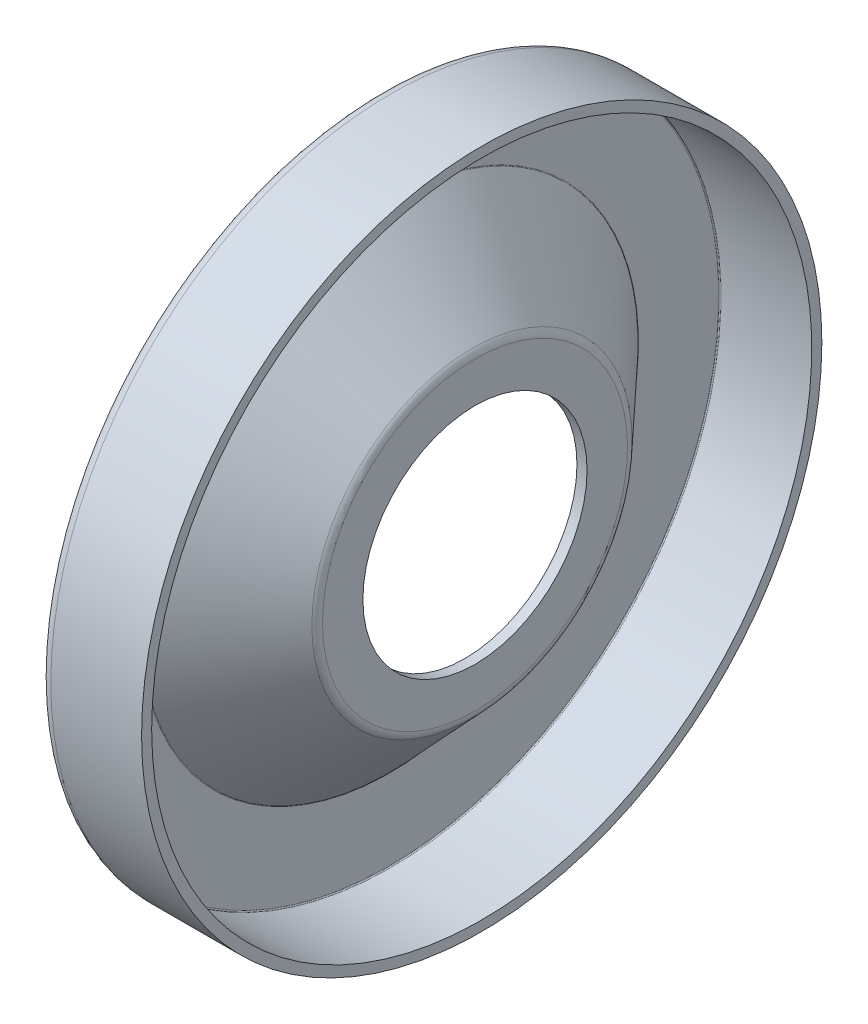
SolidWorks part; units mm, degrees
ref_plane "Alzado" through (0, 0, 0) normal (0, 0, 1) x (1, 0, 0)
ref_plane "Planta" through (0, 0, 0) normal (0, 1, 0) x (1, 0, 0)
ref_plane "Vista lateral" through (0, 0, 0) normal (1, 0, 0) x (0, 0, -1)
sketch "Croquis1" plane through (0, 0, 0) normal (0, 0, 1) x (1, 0, 0)
  line L0 (0.9, -10) -> (0.9, -13.6061)
  line L1 (0.6314, -14.2881) -> (-6.6731, -22.1212)
  line L2 (-6.7, -22.1894) -> (-6.7, -29.35)
  line L3 (-6.6, -29.45) -> (1.5, -29.45)
  line L4 (0, 0) -> (117.3844, 0) construction
  line L5 (0, -10) -> (0, -13.6061)
  line L6 (-0.0269, -13.6743) -> (-7.3314, -21.5074)
  line L7 (-7.6, -22.1894) -> (-7.6, -29.35)
  line L8 (-6.6, -30.35) -> (1.5, -30.35)
  line L9 (1.5, -29.45) -> (1.5, -30.35)
  line L10 (0.9, -10) -> (0, -10)
  arc A0 (0.9, -13.6061) -> (0.6314, -14.2881) centre (-0.1, -13.6061) cw
  arc A1 (-7.3314, -21.5074) -> (-7.6, -22.1894) centre (-6.6, -22.1894) ccw
  arc A2 (-7.6, -29.35) -> (-6.6, -30.35) centre (-6.6, -29.35) ccw
  arc A3 (0, -13.6061) -> (-0.0269, -13.6743) centre (-0.1, -13.6061) cw
  arc A4 (-6.6731, -22.1212) -> (-6.7, -22.1894) centre (-6.6, -22.1894) ccw
  arc A5 (-6.7, -29.35) -> (-6.6, -29.45) centre (-6.6, -29.35) ccw
  point P14 (0.9, -14)
  point P20 (-7.6, -30.35)
  point P25 (-6.7, -22.15)
  dimension "D11" = 1
  dimension "D12" = 0.1
  dimension "D1" = 10
  dimension "D2" = 29.45
  dimension "D3" = 0.9
  dimension "D4" = 0.9
  dimension "D5" = 0.9
  dimension "D6" = 0.9
  dimension "D7" = 7.6
  dimension "D8" = 9.1
  dimension "D9" = 28
  dimension "D10" = 43
revolve "Revolución1" add sketch "Croquis1" angle 360 about L4
